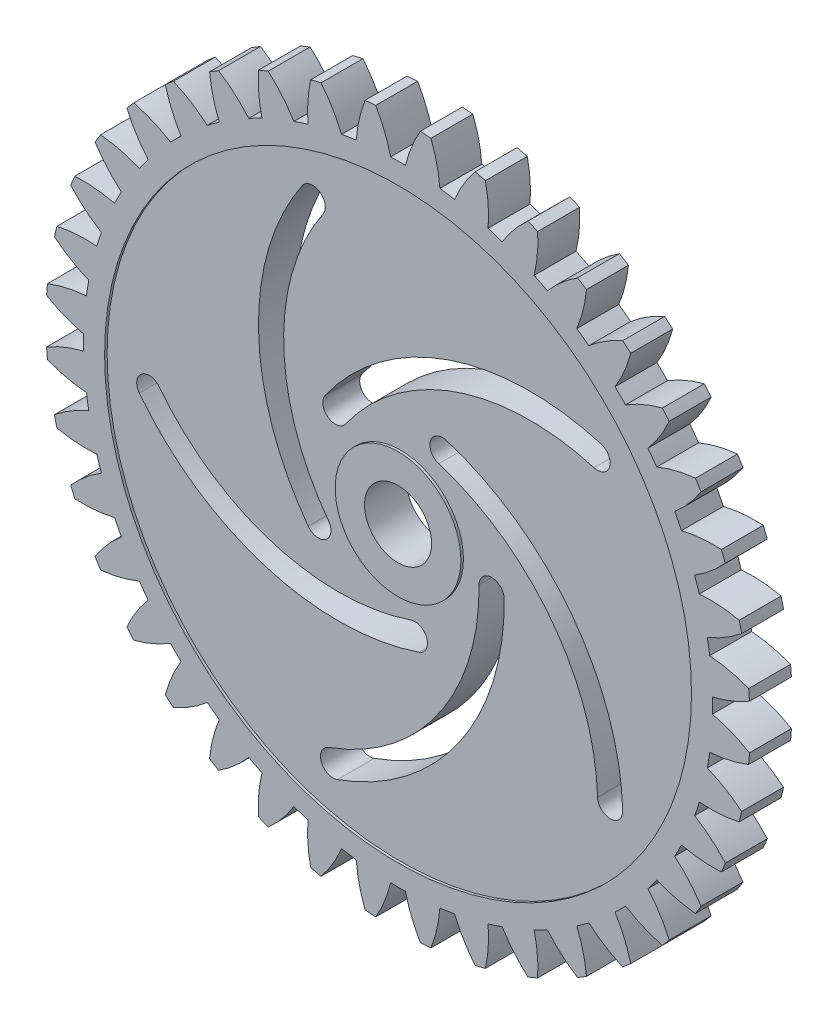
SolidWorks part; units mm, degrees
ref_plane "Front Plane" through (0, 0, 0) normal (0, 0, 1) x (1, 0, 0)
ref_plane "Top Plane" through (0, 0, 0) normal (0, 1, 0) x (1, 0, 0)
ref_plane "Right Plane" through (0, 0, 0) normal (1, 0, 0) x (0, 0, -1)
sketch "Sketch1" plane through (0, 0, 0) normal (0, 0, 1) x (1, 0, 0)
  circle A0 centre (0, 0) radius 42
  dimension "D1" = 84
extrude "Boss-Extrude1" add sketch "Sketch1" along normal mid plane 5
sketch "Sketch2" plane through (0, 0, 2.5) normal (0, 0, 1) x (1, 0, 0)
  line L0 (0, 0) -> (0, 42.025) construction
  circle A0 centre (0, 0) radius 37.5 construction
  circle A1 centre (0, 0) radius 42.025 construction
  arc A2 (0.8849, 37.4896) -> (-0.8849, 37.4896) centre (0, 0) ccw
  arc A3 (-2.6782, 41.9396) -> (2.6782, 41.9396) centre (0, 0) cw
  arc A4 (-2.6782, 41.9396) -> (-0.8849, 37.4896) centre (-16.4541, 33.8018) cw
  arc A5 (2.6782, 41.9396) -> (0.8849, 37.4896) centre (16.4541, 33.8018) ccw
  dimension "D1" = 75
  dimension "D2" = 84.05
  dimension "D3" = 1.77
  dimension "D5" = 16
  dimension "D4" = 5.36
extrude "Cut-Extrude1" cut sketch "Sketch2" against normal through all
pattern_circular "CirPattern1" count 40 over 360 about axis through (0, 0, 0) along (0, 0, 1) of "Cut-Extrude1"
sketch "Sketch3" plane through (0, 0, 2.5) normal (0, 0, 1) x (1, 0, 0)
  circle A0 centre (0, 0) radius 4
  dimension "D1" = 8
extrude "Cut-Extrude2" cut sketch "Sketch3" against normal through all
sketch "Sketch4" plane through (0, 0, 2.5) normal (0, 0, 1) x (1, 0, 0)
  circle A0 centre (0, 0) radius 7.5
  circle A1 centre (0, 0) radius 35
  dimension "D1" = 70
  dimension "D2" = 15
extrude "Cut-Extrude3" cut sketch "Sketch4" against normal blind 0.3
mirror "Mirror1" about plane through (0, 0, 0) normal (0, 0, 1) of "Cut-Extrude3"
sketch "Sketch5" plane through (0, 0, 2.2) normal (0, 0, 1) x (1, 0, 0)
  arc A0 (5, 9.798) -> (25, -16.5831) centre (-3.488, -17.4087) cw construction
  arc A1 (26.4994, -16.5397) -> (5.4467, 11.2299) centre (-3.488, -17.4087) ccw
  arc A2 (23.5006, -16.6266) -> (4.5533, 8.366) centre (-3.488, -17.4087) ccw
  arc A3 (23.5006, -16.6266) -> (26.4994, -16.5397) centre (25, -16.5831) ccw
  arc A4 (5.4467, 11.2299) -> (4.5533, 8.366) centre (5, 9.798) ccw
  arc A9 (10.8635, -1.7275) -> (-8.0461, -28.9009) centre (-17.6345, -2.0623) cw construction
  arc A10 (-7.5414, -30.3134) -> (12.3634, -1.7099) centre (-17.6345, -2.0623) ccw
  arc A11 (-8.5507, -27.4883) -> (9.3636, -1.7452) centre (-17.6345, -2.0623) ccw
  arc A12 (-8.5507, -27.4883) -> (-7.5414, -30.3134) centre (-8.0461, -28.9009) ccw
  arc A13 (12.3634, -1.7099) -> (9.3636, -1.7452) centre (10.8635, -1.7275) ccw
  arc A14 (1.714, -10.8656) -> (-29.9727, -1.2786) centre (-7.4107, 16.1342) cw construction
  arc A15 (-31.1602, -2.1951) -> (2.1943, -12.2867) centre (-7.4107, 16.1342) ccw
  arc A16 (-28.7853, -0.3621) -> (1.2338, -9.4446) centre (-7.4107, 16.1342) ccw
  arc A17 (-28.7853, -0.3621) -> (-31.1602, -2.1951) centre (-29.9727, -1.2786) ccw
  arc A18 (2.1943, -12.2867) -> (1.2338, -9.4446) centre (1.714, -10.8656) ccw
  arc A19 (-9.8042, -4.9878) -> (-10.4781, 28.1107) centre (13.0545, 12.0337) cw construction
  arc A20 (-11.7167, 28.9568) -> (-11.0073, -5.8837) centre (13.0545, 12.0337) ccw
  arc A21 (-9.2396, 27.2645) -> (-8.6011, -4.0919) centre (13.0545, 12.0337) ccw
  arc A22 (-9.2396, 27.2645) -> (-11.7167, 28.9568) centre (-10.4781, 28.1107) ccw
  arc A23 (-11.0073, -5.8837) -> (-8.6011, -4.0919) centre (-9.8042, -4.9878) ccw
  arc A24 (-7.7733, 7.783) -> (23.4969, 18.6519) centre (15.4788, -8.6969) cw construction
  arc A25 (23.9189, 20.0914) -> (-8.9971, 8.6504) centre (15.4788, -8.6969) ccw
  arc A26 (23.0749, 17.2125) -> (-6.5495, 6.9157) centre (15.4788, -8.6969) ccw
  arc A27 (23.0749, 17.2125) -> (23.9189, 20.0914) centre (23.4969, 18.6519) ccw
  arc A28 (-8.9971, 8.6504) -> (-6.5495, 6.9157) centre (-7.7733, 7.783) ccw
  point P3 (19.2231, -0.1909)
  point P15 (5.7587, -18.3413)
  point P23 (-15.6641, -11.1446)
  point P31 (-15.4396, 11.4536)
  point P39 (6.1219, 18.2233)
  point P44 (0, 0)
  dimension "D1" = 1.5
  dimension "D2" = 30
  dimension "D3" = 25
  dimension "D4" = 30
  dimension "D5" = 11
  dimension "D6" = 5
  dimension "D7" = 5
extrude "Cut-Extrude4" cut sketch "Sketch5" against normal through all
